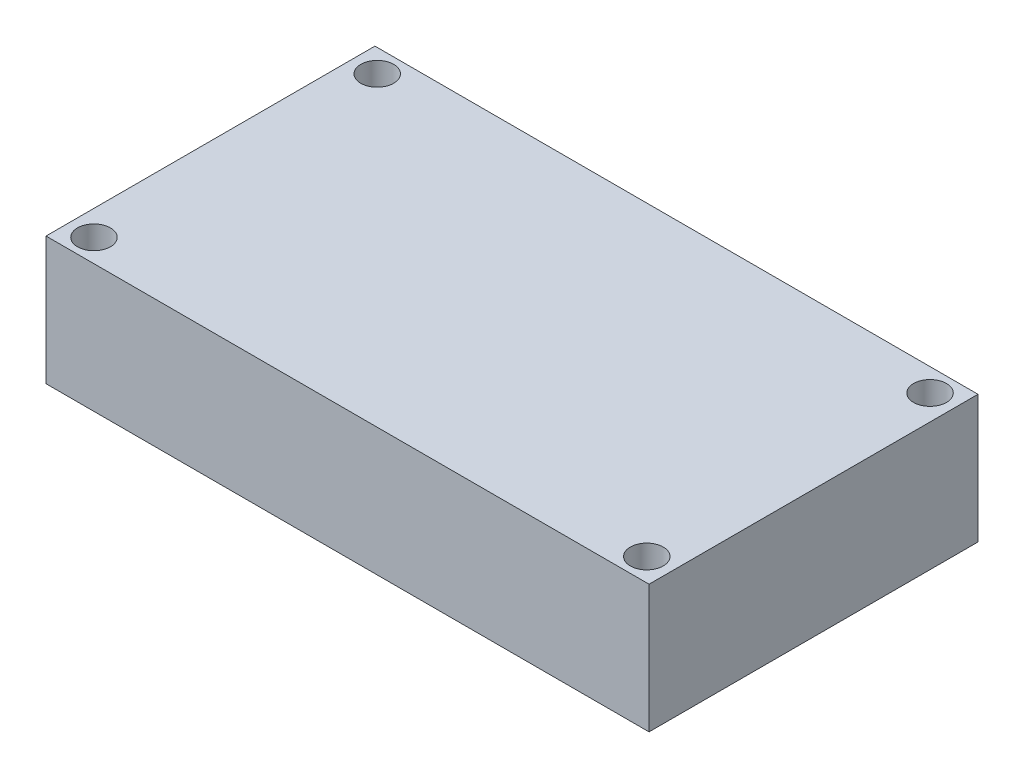
SolidWorks part; units mm, degrees
ref_plane "Front Plane" through (0, 0, 0) normal (0, 0, 1) x (1, 0, 0)
ref_plane "Top Plane" through (0, 0, 0) normal (0, 1, 0) x (1, 0, 0)
ref_plane "Right Plane" through (0, 0, 0) normal (1, 0, 0) x (0, 0, -1)
sketch "Sketch2" plane through (0, 0, 0) normal (0, 1, 0) x (1, 0, 0)
  line L1 (0, 0) -> (66, 0)
  line L2 (0, 0) -> (0, 36)
  line L3 (0, 36) -> (66, 36)
  line L4 (66, 0) -> (66, 36)
  dimension "D1" = 36
  dimension "D2" = 66
extrude "Boss-Extrude1" add sketch "Sketch2" along normal blind 14
sketch "Sketch3" plane through (0, 14, 0) normal (0, 1, 0) x (1, 0, 0)
  line L0 (0, 18) -> (66, 18) construction
  line L1 (0, 36) -> (0, 0) construction
  line L2 (66, 0) -> (66, 36) construction
  line L4 (2.75, 33.5) -> (63.25, 33.5) construction
  line L5 (2.75, 33.5) -> (2.75, 2.5) construction
  line L6 (2.75, 2.5) -> (63.25, 2.5) construction
  line L7 (63.25, 33.5) -> (63.25, 2.5) construction
  line L8 (2.75, 33.5) -> (63.25, 2.5) construction
  line L9 (2.75, 2.5) -> (63.25, 33.5) construction
  point P6 (33, 18)
  point P7 (63.25, 2.5)
  point P8 (2.75, 33.5)
  point P9 (2.75, 2.5)
  point P10 (63.25, 33.5)
  dimension "D1" = 31
  dimension "D2" = 60.5
hole_wizard "M3 Clearance Hole1" positions "Sketch3" profile "Sketch4" hole size "M3" standard "ANSI Metric"
sketch "Sketch4" plane through (63.25, 14, -33.5) normal (1, 0, 0) x (0, 0, 1)
  line L0 (0, 0) -> (0, 14)
  line L1 (0, 14) -> (1.8, 14)
  line L2 (1.8, 14) -> (1.8, 0)
  line L5 (1.8, 0) -> (0, 0)
  line L11 (0, -6.35) -> (0, 107.95) construction
  dimension "Thru Hole Dia." = 3.6
  dimension "Thru Hole Depth" = 14
